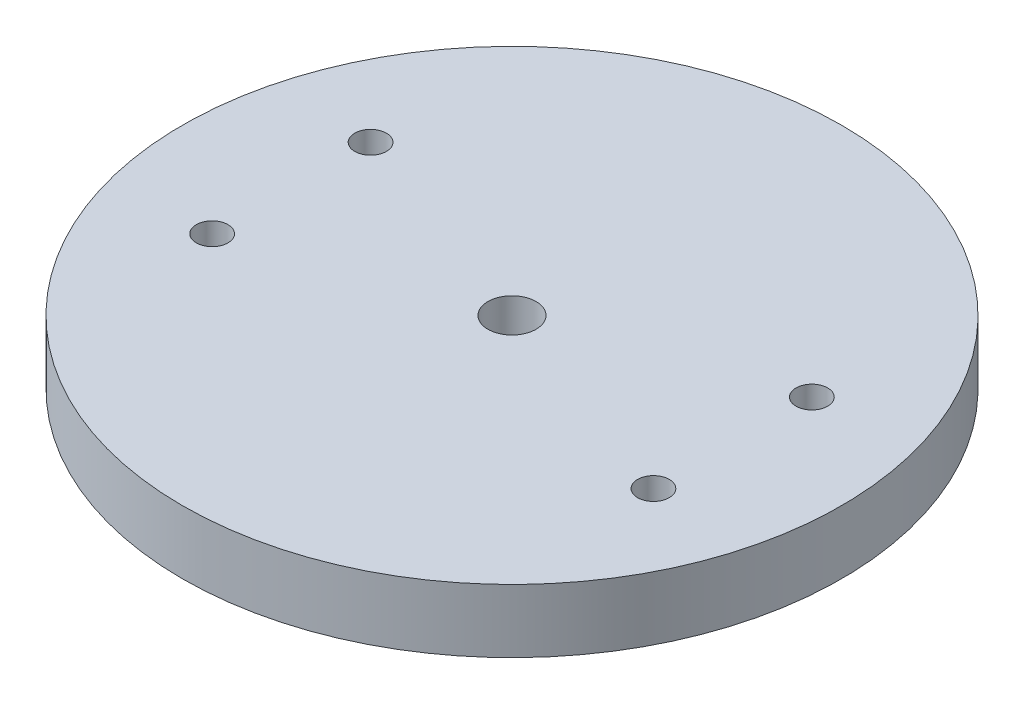
SolidWorks part; units mm, degrees
ref_plane "Front Plane" through (0, 0, 0) normal (0, 0, 1) x (1, 0, 0)
ref_plane "Top Plane" through (0, 0, 0) normal (0, 1, 0) x (1, 0, 0)
ref_plane "Right Plane" through (0, 0, 0) normal (1, 0, 0) x (0, 0, -1)
sketch "Sketch1" plane through (0, 0, 0) normal (0, 1, 0) x (1, 0, 0)
  circle A0 centre (0, 0) radius 66.04
  dimension "D1" = 132.08
extrude "Boss-Extrude1" add sketch "Sketch1" along normal blind 12.7
sketch "Sketch3" plane through (0, 12.7, 0) normal (0, 1, 0) x (1, 0, 0)
  circle A0 centre (0, 0) radius 63.5
  dimension "D1" = 127
sketch "Sketch2" plane through (0, 12.7, 0) normal (0, 1, 0) x (1, 0, 0)
  line L0 (-72.7941, 0) -> (72.3878, 0) construction
  line L1 (0, 70.7385) -> (0, -72.4581) construction
  circle A0 centre (-44.2148, 15.875) radius 3.175
  circle A1 centre (-44.2148, -15.875) radius 3.175
  circle A2 centre (44.2148, -15.875) radius 3.175
  circle A3 centre (44.2148, 15.875) radius 3.175
  dimension "D1" = 6.35
  dimension "D2" = 15.875
extrude "Cut-Extrude1" cut sketch "Sketch2" against normal through all and the other way through all
sketch "Sketch4" plane through (0, 0, 0) normal (0, -1, 0) x (1, 0, 0)
  circle A0 centre (0, 0) radius 4.826
  dimension "D1" = 9.652
extrude "Cut-Extrude2" cut sketch "Sketch4" against normal through all
